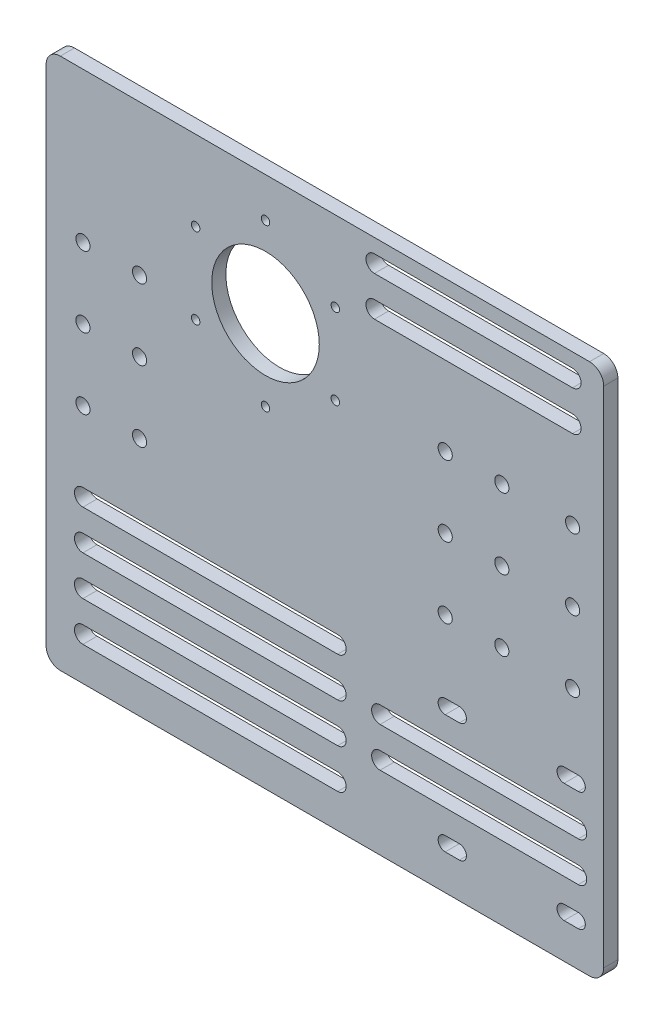
SolidWorks part; units mm, degrees
ref_plane "前视基准面" through (0, 0, 0) normal (0, 0, 1) x (1, 0, 0)
ref_plane "上视基准面" through (0, 0, 0) normal (0, 1, 0) x (1, 0, 0)
ref_plane "右视基准面" through (0, 0, 0) normal (1, 0, 0) x (0, 0, -1)
sketch "草图1" plane through (0, 0, 0) normal (0, 0, 1) x (1, 0, 0)
  line L0 (-73, 60) -> (-73, 35) construction
  line L2 (-86, 75) -> (-86, -75)
  line L3 (-86, -75) -> (86, -75)
  line L6 (-86, 75) -> (-86, 35) construction
  line L7 (-86, 35) -> (-8.5, 35) construction
  line L8 (-8.5, 75) -> (-8.5, 35) construction
  line L10 (-86, 75) -> (-86, 60) construction
  line L11 (-86, 60) -> (-73, 60) construction
  line L12 (-73, 75) -> (-73, 60) construction
  line L13 (-73, 60) -> (-53, 60) construction
  line L14 (75, 60) -> (55, 60) construction
  line L17 (86, 60) -> (75, 60) construction
  line L20 (55, 60) -> (100, 60) construction
  line L21 (86, -75) -> (68, -75) construction
  line L29 (-86, 75) -> (-86, 113)
  line L30 (-86, 113) -> (111, 113)
  line L32 (111, 75) -> (111, -75)
  line L33 (111, -75) -> (86, -75)
  line L34 (111, 113) -> (111, 75)
  line L35 (-73, -18) -> (17, -18) construction
  line L36 (55, -18) -> (60, -18) construction
  line L37 (55, -15.5) -> (60, -15.5)
  line L38 (55, -20.5) -> (60, -20.5)
  line L39 (55, -60) -> (60, -60) construction
  line L40 (55, -57.5) -> (60, -57.5)
  line L41 (55, -62.5) -> (60, -62.5)
  line L42 (97, -18) -> (102, -18) construction
  line L43 (97, -15.5) -> (102, -15.5)
  line L44 (97, -20.5) -> (102, -20.5)
  line L45 (97, -60) -> (102, -60) construction
  line L46 (97, -57.5) -> (102, -57.5)
  line L47 (97, -62.5) -> (102, -62.5)
  line L48 (-73, -15) -> (17, -15)
  line L49 (-73, -21) -> (17, -21)
  line L50 (-73, -60) -> (17, -60) construction
  line L51 (-73, -57) -> (17, -57)
  line L52 (-73, -63) -> (17, -63)
  line L53 (-73, -32) -> (17, -32) construction
  line L54 (-73, -29) -> (17, -29)
  line L55 (-73, -35) -> (17, -35)
  line L56 (-73, -46) -> (17, -46) construction
  line L57 (-73, -43) -> (17, -43)
  line L58 (-73, -49) -> (17, -49)
  line L59 (100, 105) -> (30, 105) construction
  line L60 (100, 102) -> (30, 102)
  line L61 (100, 108) -> (30, 108)
  line L62 (100, 91) -> (30, 91) construction
  line L63 (100, 88) -> (30, 88)
  line L64 (100, 94) -> (30, 94)
  line L65 (102, -32) -> (32, -32) construction
  line L68 (102, -35) -> (32, -35)
  line L69 (102, -29) -> (32, -29)
  line L70 (102, -46) -> (32, -46) construction
  line L71 (102, -49) -> (32, -49)
  line L72 (102, -43) -> (32, -43)
  circle A0 centre (-73, 60) radius 2.5
  circle A1 centre (-53, 60) radius 2.5
  circle A3 centre (-73, 35) radius 2.5
  circle A4 centre (-53, 10) radius 2.5
  circle A5 centre (-73, 10) radius 2.5
  circle A14 centre (75, 60) radius 2.5
  circle A15 centre (75, 35) radius 2.5
  circle A16 centre (75, 10) radius 2.5
  circle A17 centre (55, 60) radius 2.5
  circle A18 centre (55, 35) radius 2.5
  circle A19 centre (55, 10) radius 2.5
  circle A24 centre (-53, 35) radius 2.5
  circle A25 centre (100, 60) radius 2.5
  circle A26 centre (100, 35) radius 2.5
  circle A27 centre (100, 10) radius 2.5
  circle A32 centre (55, -18) radius 2.5 construction
  circle A35 centre (97, -60) radius 2.5 construction
  arc A46 (55, -15.5) -> (55, -20.5) centre (55, -18) ccw
  arc A47 (60, -20.5) -> (60, -15.5) centre (60, -18) ccw
  arc A48 (55, -57.5) -> (55, -62.5) centre (55, -60) ccw
  arc A49 (60, -62.5) -> (60, -57.5) centre (60, -60) ccw
  arc A50 (97, -15.5) -> (97, -20.5) centre (97, -18) ccw
  arc A51 (102, -20.5) -> (102, -15.5) centre (102, -18) ccw
  arc A52 (97, -57.5) -> (97, -62.5) centre (97, -60) ccw
  arc A53 (102, -62.5) -> (102, -57.5) centre (102, -60) ccw
  circle A61 centre (-8.5, 70.5) radius 28.5 construction
  circle A62 centre (-8.5, 99) radius 1.5
  circle A63 centre (16.1817, 84.75) radius 1.5
  circle A64 centre (16.1817, 56.25) radius 1.5
  circle A65 centre (-8.5, 42) radius 1.5
  circle A66 centre (-33.1817, 56.25) radius 1.5
  circle A67 centre (-33.1817, 84.75) radius 1.5
  circle A68 centre (-8.5, 70.5) radius 19
  arc A69 (-73, -15) -> (-73, -21) centre (-73, -18) ccw
  arc A70 (17, -21) -> (17, -15) centre (17, -18) ccw
  arc A71 (-73, -57) -> (-73, -63) centre (-73, -60) ccw
  arc A72 (17, -63) -> (17, -57) centre (17, -60) ccw
  arc A73 (-73, -29) -> (-73, -35) centre (-73, -32) ccw
  arc A74 (17, -35) -> (17, -29) centre (17, -32) ccw
  arc A75 (-73, -43) -> (-73, -49) centre (-73, -46) ccw
  arc A76 (17, -49) -> (17, -43) centre (17, -46) ccw
  arc A77 (100, 102) -> (100, 108) centre (100, 105) ccw
  arc A78 (30, 108) -> (30, 102) centre (30, 105) ccw
  arc A79 (100, 88) -> (100, 94) centre (100, 91) ccw
  arc A80 (30, 94) -> (30, 88) centre (30, 91) ccw
  arc A83 (102, -35) -> (102, -29) centre (102, -32) ccw
  arc A84 (32, -29) -> (32, -35) centre (32, -32) ccw
  arc A85 (102, -49) -> (102, -43) centre (102, -46) ccw
  arc A86 (32, -43) -> (32, -49) centre (32, -46) ccw
  point P52 (99.5, -18)
  point P53 (-8.5, 70.5)
  point P55 (99.5, -60)
  point P64 (-28, -18)
  point P69 (57.5, -18)
  point P77 (57.5, -60)
  point P95 (-28, -60)
  point P104 (-28, -32)
  point P113 (-28, -46)
  point P120 (65, 105)
  point P127 (65, 91)
  point P134 (67, -32)
  point P141 (67, -46)
  dimension "D5" = 45
  dimension "D6" = 13
  dimension "D7" = 90
  dimension "D8" = 25
  dimension "D9" = 25
  dimension "D2" = 11
  dimension "D10" = 53
  dimension "D11" = 57
  dimension "D12" = 25
  dimension "D13" = 5
  dimension "D14" = 15
  dimension "D15" = 15
  dimension "D16" = 5
  dimension "D17" = 57
  dimension "D18" = 56
  dimension "D19" = 3
  dimension "D20" = 77.5
  dimension "D4" = 6
  dimension "D22" = 42.5
  dimension "D25" = 53
  dimension "D30" = 3
  dimension "D31" = 70
  dimension "D32" = 11
  dimension "D35" = 70
  dimension "D37" = 9
  dimension "D3" = 25
  dimension "D21" = 42
  dimension "D23" = 188
  dimension "D24" = 197
  dimension "D26" = 42
  dimension "D27" = 14
  dimension "D28" = 14
  dimension "D29" = 15
  dimension "D33" = 8
  dimension "D34" = 14
  dimension "D36" = 9
extrude "凸台-拉伸1" add sketch "草图1" along normal blind 5
fillet "圆角1" radius 5 4 edges at (-86, -75, 2.5) (111, -75, 2.5) (111, 113, 2.5) (-86, 113, 2.5)
